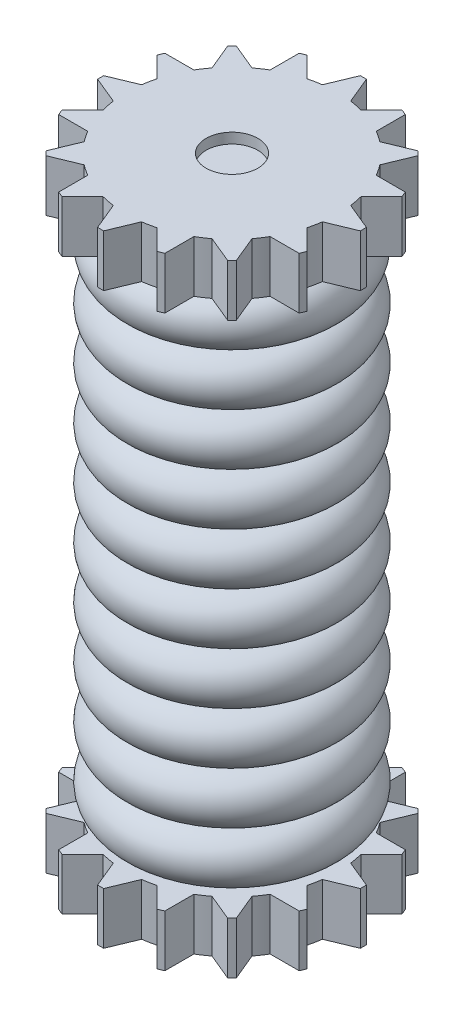
SolidWorks part; units mm, degrees
ref_plane "Front Plane" through (0, 0, 0) normal (1, 0, 0) x (0, 1, 0)
ref_plane "Top Plane" through (0, 0, 0) normal (0, 0, 1) x (0, 1, 0)
ref_plane "Right Plane" through (0, 0, 0) normal (0, 1, 0) x (-1, 0, 0)
sketch "Sketch6" plane through (0, 0, 0) normal (0, 0, 1) x (0, 1, 0)
  line L1 (0, 0) -> (100, 0)
  line L2 (0, 0) -> (0, -16.625)
  line L3 (0, -16.625) -> (100, -16.625)
  line L4 (100, 0) -> (100, -16.625)
  arc A0 (0, -16.625) -> (10, -16.625) centre (5, -16.625) ccw
  arc A1 (10, -16.625) -> (20, -16.625) centre (15, -16.625) ccw
  arc A2 (20, -16.625) -> (30, -16.625) centre (25, -16.625) ccw
  arc A3 (30, -16.625) -> (40, -16.625) centre (35, -16.625) ccw
  arc A4 (40, -16.625) -> (50, -16.625) centre (45, -16.625) ccw
  arc A5 (50, -16.625) -> (60, -16.625) centre (55, -16.625) ccw
  arc A6 (60, -16.625) -> (70, -16.625) centre (65, -16.625) ccw
  arc A7 (70, -16.625) -> (80, -16.625) centre (75, -16.625) ccw
  arc A8 (80, -16.625) -> (90, -16.625) centre (85, -16.625) ccw
  arc A9 (90, -16.625) -> (100, -16.625) centre (95, -16.625) ccw
  dimension "D3" = 5
  dimension "D1" = 16.625
  dimension "D2" = 10
  dimension "D4" = 100
revolve "Revolve1" add sketch "Sketch6" angle 360 about L1
sketch "Sketch3" plane through (0, 0, 0) normal (0, -1, 0) x (1, 0, 0)
  line L0 (0, -57.0817) -> (0, 57.0817) construction
  line L1 (0, 25.375) -> (2.1167, 20.2647) construction
  line L2 (0, 25.375) -> (-2.1167, 20.2647) construction
  line L5 (-2.733, 20.1909) -> (2.733, 20.1909) construction
  line L32 (-2.733, 20.1909) -> (-0.5885, 25.3682)
  line L33 (2.733, 20.1909) -> (0.5885, 25.3682)
  line L34 (5.2017, 19.6998) -> (9.1643, 23.6623)
  line L35 (10.2517, 17.6081) -> (10.2517, 23.2119)
  line L36 (12.3446, 16.2096) -> (17.5219, 18.3541)
  line L37 (16.2096, 12.3446) -> (18.3541, 17.5219)
  line L38 (17.6081, 10.2517) -> (23.2119, 10.2517)
  line L39 (19.6998, 5.2017) -> (23.6623, 9.1643)
  line L40 (20.1909, 2.733) -> (25.3682, 0.5885)
  line L41 (20.1909, -2.733) -> (25.3682, -0.5885)
  line L42 (19.6998, -5.2017) -> (23.6623, -9.1643)
  line L43 (17.6081, -10.2517) -> (23.2119, -10.2517)
  line L44 (16.2096, -12.3446) -> (18.3541, -17.5219)
  line L45 (12.3446, -16.2096) -> (17.5219, -18.3541)
  line L46 (10.2517, -17.6081) -> (10.2517, -23.2119)
  line L47 (5.2017, -19.6998) -> (9.1643, -23.6623)
  line L48 (2.733, -20.1909) -> (0.5885, -25.3682)
  line L49 (-2.733, -20.1909) -> (-0.5885, -25.3682)
  line L50 (-5.2017, -19.6998) -> (-9.1643, -23.6623)
  line L51 (-10.2517, -17.6081) -> (-10.2517, -23.2119)
  line L52 (-12.3446, -16.2096) -> (-17.5219, -18.3541)
  line L53 (-16.2096, -12.3446) -> (-18.3541, -17.5219)
  line L54 (-17.6081, -10.2517) -> (-23.2119, -10.2517)
  line L55 (-19.6998, -5.2017) -> (-23.6623, -9.1643)
  line L56 (-20.1909, -2.733) -> (-25.3682, -0.5885)
  line L57 (-20.1909, 2.733) -> (-25.3682, 0.5885)
  line L58 (-19.6998, 5.2017) -> (-23.6623, 9.1643)
  line L59 (-17.6081, 10.2517) -> (-23.2119, 10.2517)
  line L60 (-16.2096, 12.3446) -> (-18.3541, 17.5219)
  line L61 (-12.3446, 16.2096) -> (-17.5219, 18.3541)
  line L62 (-10.2517, 17.6081) -> (-10.2517, 23.2119)
  line L63 (-5.2017, 19.6998) -> (-9.1643, 23.6623)
  arc A28 (-16.2096, 12.3446) -> (-17.6081, 10.2517) centre (0, 0) ccw
  arc A29 (-23.2119, 10.2517) -> (-23.6623, 9.1643) centre (0, 0) ccw
  arc A30 (-17.5219, 18.3541) -> (-18.3541, 17.5219) centre (0, 0) ccw
  arc A31 (-10.2517, 17.6081) -> (-12.3446, 16.2096) centre (0, 0) ccw
  arc A32 (-9.1643, 23.6623) -> (-10.2517, 23.2119) centre (0, 0) ccw
  arc A33 (0.5885, 25.3682) -> (-0.5885, 25.3682) centre (0, 0) ccw
  arc A34 (10.2517, 23.2119) -> (9.1643, 23.6623) centre (0, 0) ccw
  arc A35 (-2.733, 20.1909) -> (-5.2017, 19.6998) centre (0, 0) ccw
  arc A36 (5.2017, 19.6998) -> (2.733, 20.1909) centre (0, 0) ccw
  arc A37 (18.3541, 17.5219) -> (17.5219, 18.3541) centre (0, 0) ccw
  arc A38 (12.3446, 16.2096) -> (10.2517, 17.6081) centre (0, 0) ccw
  arc A39 (17.6081, 10.2517) -> (16.2096, 12.3446) centre (0, 0) ccw
  arc A40 (23.6623, 9.1643) -> (23.2119, 10.2517) centre (0, 0) ccw
  arc A41 (25.3682, -0.5885) -> (25.3682, 0.5885) centre (0, 0) ccw
  arc A42 (23.2119, -10.2517) -> (23.6623, -9.1643) centre (0, 0) ccw
  arc A43 (20.1909, 2.733) -> (19.6998, 5.2017) centre (0, 0) ccw
  arc A44 (19.6998, -5.2017) -> (20.1909, -2.733) centre (0, 0) ccw
  arc A45 (17.5219, -18.3541) -> (18.3541, -17.5219) centre (0, 0) ccw
  arc A46 (9.1643, -23.6623) -> (10.2517, -23.2119) centre (0, 0) ccw
  arc A47 (10.2517, -17.6081) -> (12.3446, -16.2096) centre (0, 0) ccw
  arc A48 (16.2096, -12.3446) -> (17.6081, -10.2517) centre (0, 0) ccw
  arc A49 (-0.5885, -25.3682) -> (0.5885, -25.3682) centre (0, 0) ccw
  arc A50 (-10.2517, -23.2119) -> (-9.1643, -23.6623) centre (0, 0) ccw
  arc A51 (-5.2017, -19.6998) -> (-2.733, -20.1909) centre (0, 0) ccw
  arc A52 (2.733, -20.1909) -> (5.2017, -19.6998) centre (0, 0) ccw
  arc A53 (-18.3541, -17.5219) -> (-17.5219, -18.3541) centre (0, 0) ccw
  arc A54 (-23.6623, -9.1643) -> (-23.2119, -10.2517) centre (0, 0) ccw
  arc A55 (-12.3446, -16.2096) -> (-10.2517, -17.6081) centre (0, 0) ccw
  arc A56 (-17.6081, -10.2517) -> (-16.2096, -12.3446) centre (0, 0) ccw
  arc A57 (-20.1909, -2.733) -> (-19.6998, -5.2017) centre (0, 0) ccw
  arc A58 (-25.3682, 0.5885) -> (-25.3682, -0.5885) centre (0, 0) ccw
  arc A59 (-19.6998, 5.2017) -> (-20.1909, 2.733) centre (0, 0) ccw
  point P13 (0, 57.0817)
  point P17 (0, 47.4976)
  point P78 (0, 0)
  dimension "D2" = 50.75
  dimension "D1" = 40.75
  dimension "D3" = 22.5
  dimension "D4" = 22.5
  dimension "D5" = 5.466
  dimension "D6" = 16
extrude "Boss-Extrude3" add sketch "Sketch3" along normal blind 10
ref_plane "Plane1" through (0, 50, 0) normal (0, 1, 0) x (1, 0, 0)
mirror "Mirror1" about plane through (0, 50, 0) normal (0, 1, 0) of "Boss-Extrude3"
sketch "Sketch4" plane through (0, -10, 0) normal (0, -1, 0) x (1, 0, 0)
  circle A0 centre (0, 0) radius 5
  dimension "D1" = 10
extrude "Boss-Extrude4" add sketch "Sketch4" along normal blind 10
sketch "Sketch7" plane through (0, 110, 0) normal (0, 1, 0) x (-1, 0, 0)
  circle A0 centre (0, 0) radius 5
  dimension "D1" = 10
extrude "Cut-Extrude1" cut sketch "Sketch7" against normal blind 2
